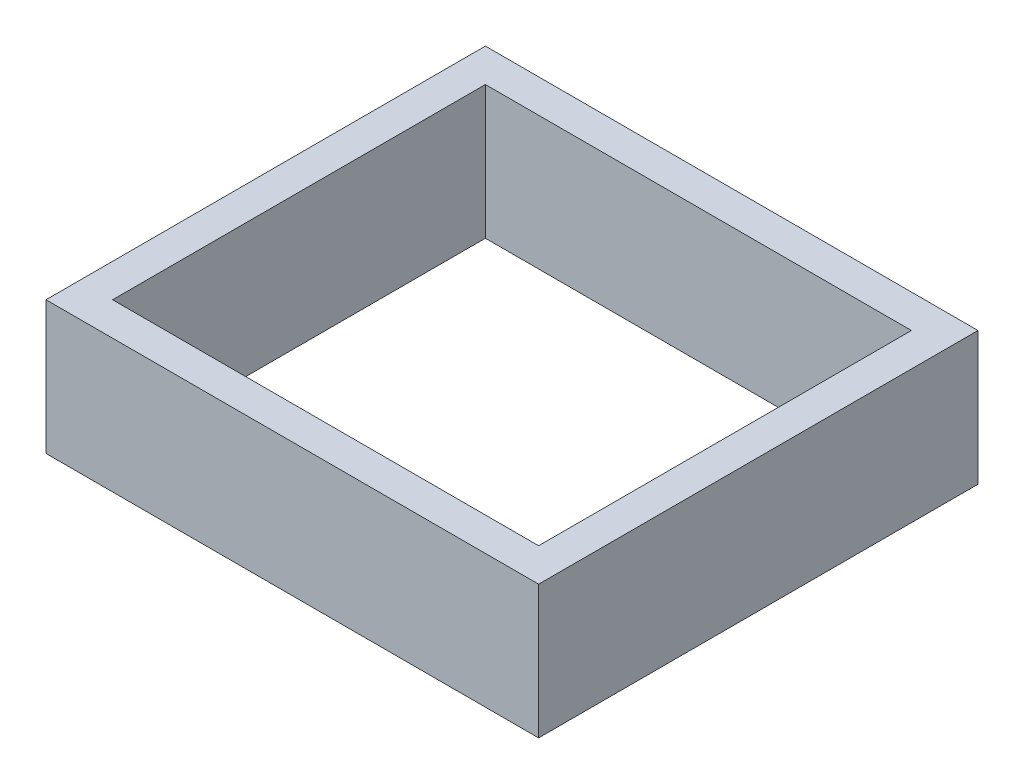
SolidWorks part; units mm, degrees
ref_plane "Ön Düzlem" through (0, 0, 0) normal (0, 0, 1) x (1, 0, 0)
ref_plane "Üst Düzlem" through (0, 0, 0) normal (0, 1, 0) x (1, 0, 0)
ref_plane "Sağ Düzlem" through (0, 0, 0) normal (1, 0, 0) x (0, 0, -1)
sketch "Çizim1" plane through (0, 0, 0) normal (0, 1, 0) x (1, 0, 0)
  line L0 (5, 61) -> (69, 61)
  line L1 (0, 0) -> (74, 0)
  line L2 (0, 0) -> (0, 66)
  line L3 (0, 66) -> (74, 66)
  line L4 (74, 0) -> (74, 66)
  line L5 (69, 5) -> (69, 61)
  line L6 (5, 5) -> (69, 5)
  line L7 (5, 5) -> (5, 61)
  dimension "D1" = 74
  dimension "D2" = 66
  dimension "D3" = 5
extrude "Yükseklik-Ekstrüzyon1" add sketch "Çizim1" along normal blind 20
